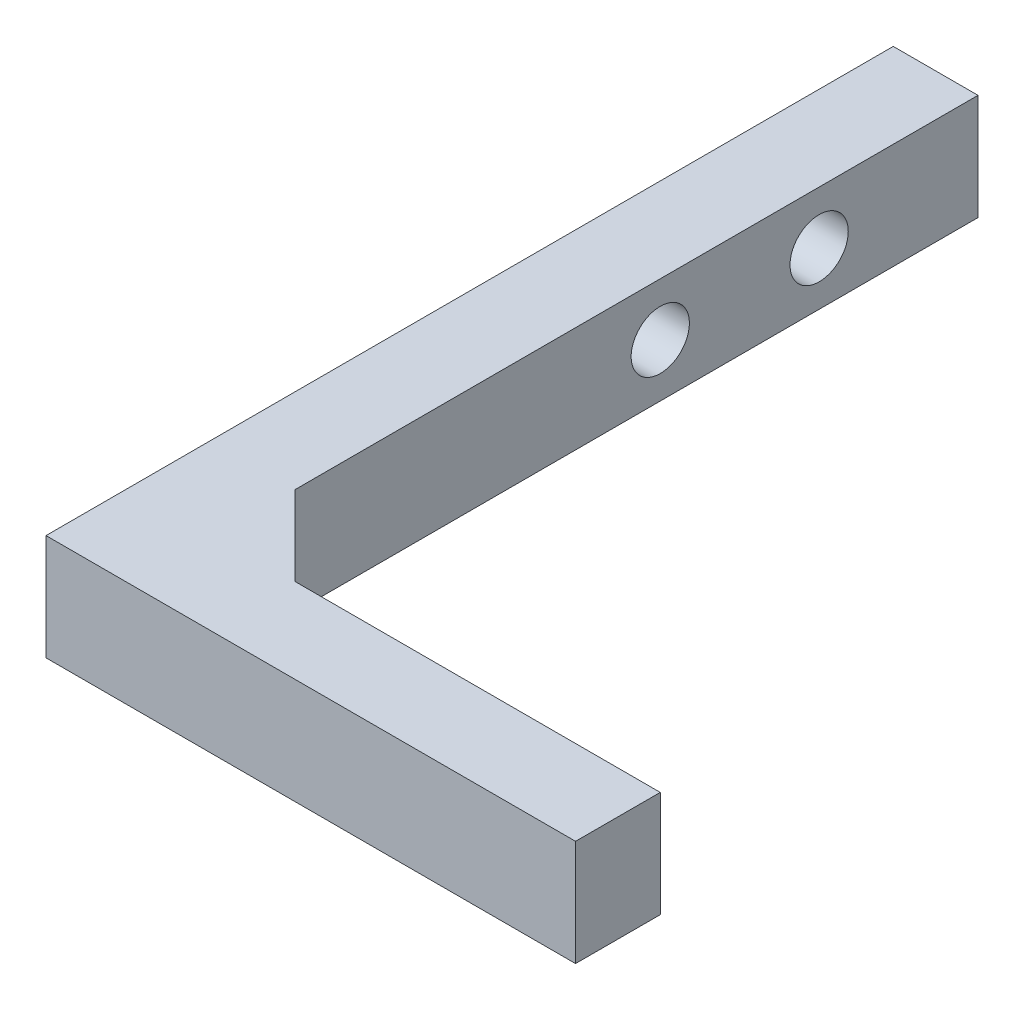
SolidWorks part; units mm, degrees
ref_plane "前视基准面" through (0, 0, 0) normal (0, 0, 1) x (1, 0, 0)
ref_plane "上视基准面" through (0, 0, 0) normal (0, 1, 0) x (1, 0, 0)
ref_plane "右视基准面" through (0, 0, 0) normal (1, 0, 0) x (0, 0, -1)
other "Configuration Table"
sketch "草图1" plane through (0, 0, 0) normal (0, 1, 0) x (1, 0, 0)
  line L1 (-18.9928, 67.3022) -> (-10.9928, 67.3022)
  line L2 (-18.9928, 67.3022) -> (-18.9928, -12.6978)
  line L3 (-18.9928, -12.6978) -> (-10.9928, -12.6978)
  line L4 (-10.9928, 67.3022) -> (-10.9928, -4.6978)
  line L5 (-18.9928, -12.6978) -> (31.0072, -12.6978)
  line L6 (-18.9928, -12.6978) -> (-18.9928, -4.6978)
  line L7 (-10.9928, -4.6978) -> (31.0072, -4.6978)
  line L8 (31.0072, -12.6978) -> (31.0072, -4.6978)
  dimension "D1" = 80
  dimension "D2" = 50
  dimension "D3" = 8
  dimension "D4" = 8
extrude "凸台-拉伸1" add sketch "草图1" along normal blind 10 contours L5 L8 L7 L4 L1 L2 L3
chamfer "倒角1" distance 7.5 angle 45 1 edges at (-10.9928, 5, 4.6978)
sketch "草图2" plane through (-10.9928, 0, 0) normal (1, 0, 0) x (0, 0, -1)
  line L0 (-12.6978, 10) -> (-12.6978, 0) construction
  circle A0 centre (37.3022, 5) radius 2.75
  circle A1 centre (52.3022, 5) radius 2.75
  point P6 (53.0088, 5)
  dimension "D3" = 5.5
  dimension "D4" = 5.5
  dimension "D1" = 50
  dimension "D2" = 15
extrude "切除-拉伸1" cut sketch "草图2" against normal through all
